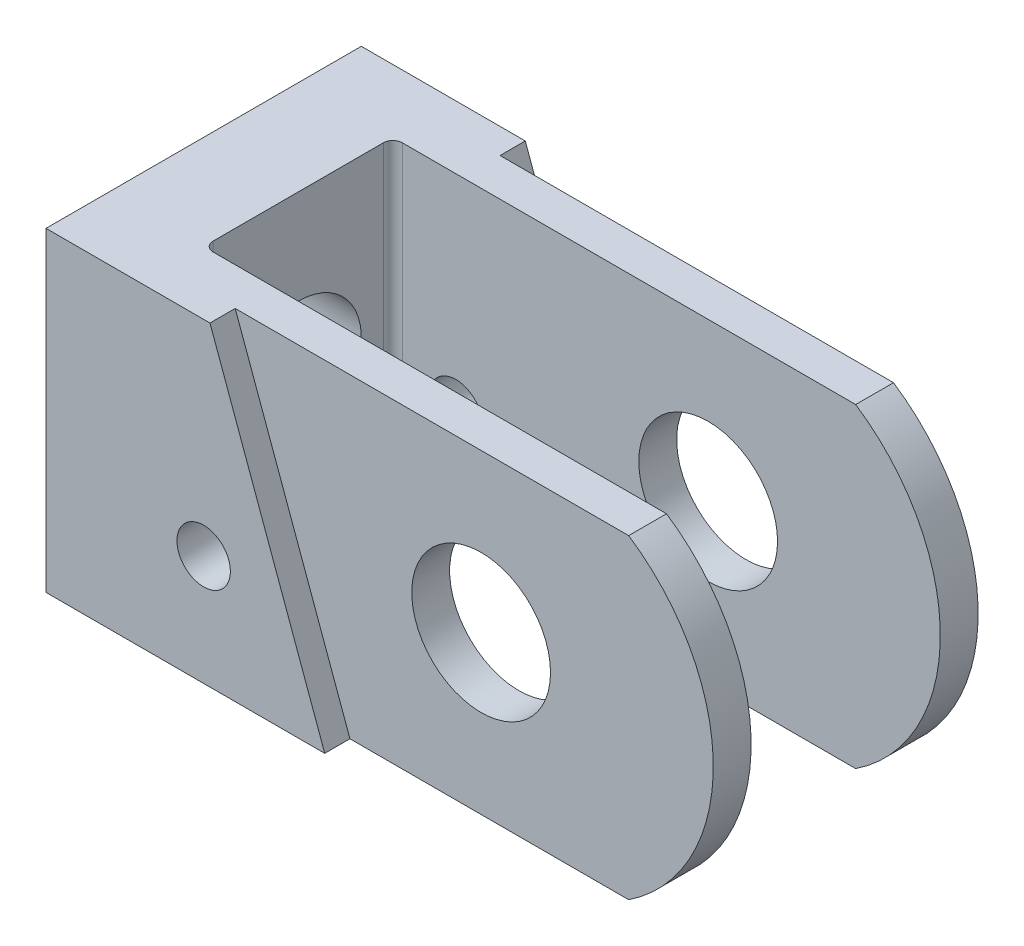
SolidWorks part; units mm, degrees
ref_plane "Alzado" through (0, 0, 0) normal (0, 0, 1) x (1, 0, 0)
ref_plane "Planta" through (0, 0, 0) normal (0, 1, 0) x (1, 0, 0)
ref_plane "Vista lateral" through (0, 0, 0) normal (1, 0, 0) x (0, 0, -1)
sketch "Croquis2" plane through (0, 0, 0) normal (0, 1, 0) x (1, 0, 0)
  line L0 (-34.1489, 19.6809) -> (-34.1489, -30.3191)
  line L1 (-34.1489, -30.3191) -> (0, -30.3191)
  line L2 (0, -30.3191) -> (0, -26.3191)
  line L3 (0, -26.3191) -> (67.6596, -26.3191)
  line L4 (67.6596, -26.3191) -> (67.6596, -20.3191)
  line L5 (67.6596, -20.3191) -> (-17.6489, -20.3191)
  line L6 (-34.1489, -5.3191) -> (0, -5.3191) construction
  line L7 (67.6596, 9.6809) -> (-17.6489, 9.6809)
  line L8 (0, 15.6809) -> (67.6596, 15.6809)
  line L9 (0, 19.6809) -> (0, 15.6809)
  line L10 (-34.1489, 19.6809) -> (0, 19.6809)
  line L11 (67.6596, 15.6809) -> (67.6596, 9.6809)
  line L12 (-19.1489, 8.1809) -> (-19.1489, -18.8191)
  arc A0 (-17.6489, -20.3191) -> (-19.1489, -18.8191) centre (-17.6489, -18.8191) cw
  arc A1 (-17.6489, 9.6809) -> (-19.1489, 8.1809) centre (-17.6489, 8.1809) ccw
  point P17 (-19.1489, -20.3191)
  point P20 (-19.1489, 9.6809)
  dimension "D5" = 1.5
  dimension "D1" = 30
  dimension "D2" = 15
  dimension "D3" = 6
  dimension "D4" = 50
extrude "Saliente-Extruir1" add sketch "Croquis2" along normal blind 50
sketch "Croquis3" plane through (-34.1489, 0, 0) normal (-1, 0, 0) x (0, 0, 1)
  line L0 (5.3191, 50) -> (5.3191, 0) construction
  line L1 (-19.6809, 50) -> (30.3191, 50) construction
  line L2 (-19.6809, 0) -> (30.3191, 0) construction
  circle A0 centre (5.3191, 25) radius 17.5
  dimension "D1" = 35
extrude "Cortar-Extruir1" cut sketch "Croquis3" against normal blind 2
sketch "Croquis4" plane through (-32.1489, 0, 0) normal (-1, 0, 0) x (0, 0, 1)
  circle A0 centre (5.3191, 25) radius 10
  dimension "D1" = 20
extrude "Cortar-Extruir2" cut sketch "Croquis4" against normal blind 25
sketch "Croquis5" plane through (0, 0, 26.3191) normal (0, 0, 1) x (1, 0, 0)
  line L1 (0, 50) -> (67.6596, 50) construction
  line L4 (30.8511, 49.0417) -> (30.8511, 50)
  circle A0 centre (30.8511, 25) radius 11
  dimension "D2" = 22
extrude "Cortar-Extruir3" cut sketch "Croquis5" against normal through all contours A0
sketch "Croquis6" plane through (0, 0, 26.3191) normal (0, 0, 1) x (1, 0, 0)
  line L0 (75.5928, 25) -> (67.6596, 25) construction
  line L1 (75.5928, 50) -> (75.5928, 0)
  line L2 (75.5928, 0) -> (54.2427, 0)
  line L3 (0, 0) -> (67.6596, 0) construction
  line L4 (75.5928, 50) -> (54.2427, 50)
  arc A3 (54.2427, 0) -> (54.2427, 50) centre (37.6596, 25) ccw
extrude "Cortar-Extruir4" cut sketch "Croquis6" against normal through all
sketch "Croquis7" plane through (0, 0, 30.3191) normal (0, 0, 1) x (1, 0, 0)
  line L0 (-34.1489, 50) -> (-34.1489, 0) construction
  line L1 (-34.1489, 0) -> (0, 0) construction
  line L2 (-34.1489, 50) -> (-8.1489, 50)
  line L3 (0, 50) -> (54.2427, 50) construction
  line L6 (10.0496, 0) -> (-34.1489, 0)
  line L7 (-34.1489, 0) -> (-34.1489, 50)
  line L8 (-8.1489, 50) -> (10.0496, 0)
  circle A0 centre (-9.1489, 17.5) radius 2.5
  dimension "D3" = 5
  dimension "D1" = 25
  dimension "D2" = 17.5
  dimension "D4" = 26
  dimension "D5" = 110
extrude "Saliente-Extruir6" add sketch "Croquis7" against normal blind 4
sketch "Croquis8" plane through (0, 0, 30.3191) normal (0, 0, 1) x (1, 0, 0)
  line L0 (0, 27.611) -> (-8.1489, 50)
  line L1 (-34.1489, 50) -> (0, 50) construction
  line L3 (-8.1489, 50) -> (0, 50)
  line L4 (0, 50) -> (0, 27.611)
extrude "Cortar-Extruir6" cut sketch "Croquis8" against normal blind 4
sketch "Croquis10" plane through (0, 0, 30.3191) normal (0, 0, 1) x (1, 0, 0)
  line L0 (-34.1489, 0) -> (10.0496, 0) construction
  line L1 (-34.1489, 50) -> (-34.1489, 0) construction
  circle A0 centre (-9.1489, 17.5) radius 4.2371
  dimension "D1" = 17.5
  dimension "D2" = 25
extrude "Cortar-Extruir7" cut sketch "Croquis10" against normal through all
sketch "Croquis11" plane through (0, 0, -19.6809) normal (0, 0, -1) x (-1, 0, 0)
  line L10 (8.1489, 50) -> (-10.0496, 0)
  line L11 (-10.0496, 0) -> (8.1489, 50) construction
  line L12 (-10.0496, 0) -> (19.1489, 0)
  line L13 (19.1489, 0) -> (19.1489, 50)
  line L14 (19.1489, 50) -> (8.1489, 50)
extrude "Saliente-Extruir8" add sketch "Croquis11" against normal blind 4
sketch "Croquis13" plane through (0, 0, -19.6809) normal (0, 0, -1) x (-1, 0, 0)
  line L0 (0, 50) -> (0, 27.611)
  line L1 (0, 27.611) -> (8.1489, 50)
  line L2 (8.1489, 50) -> (0, 50)
extrude "Cortar-Extruir10" cut sketch "Croquis13" against normal blind 4
